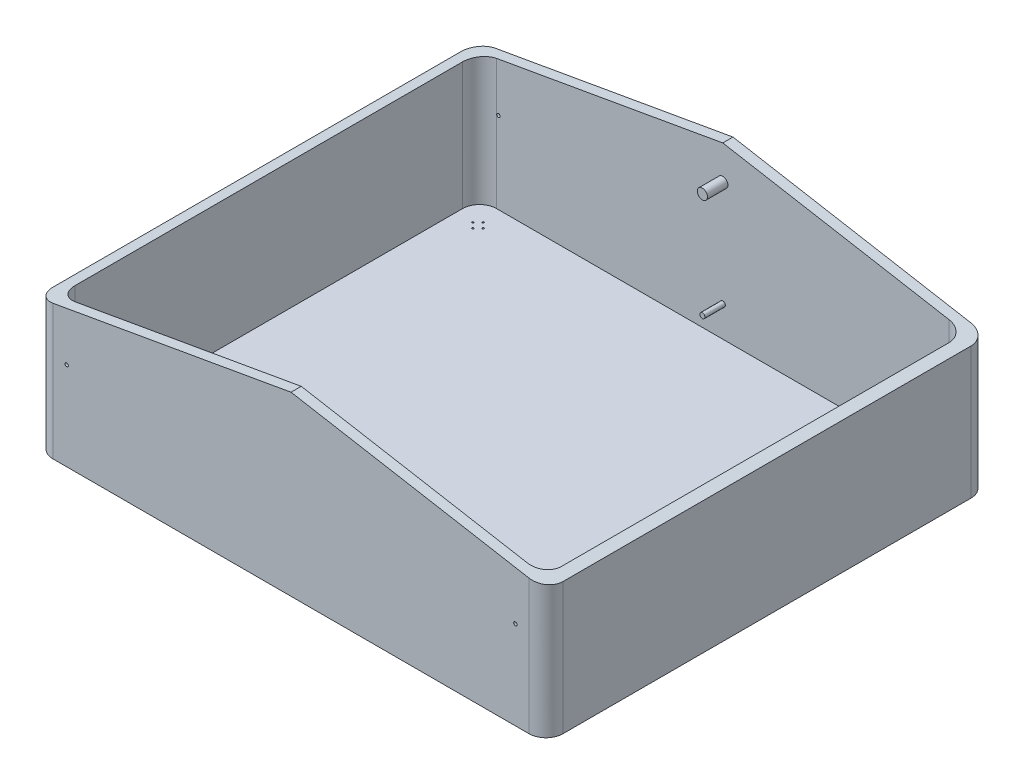
SolidWorks part; units mm, degrees
ref_plane "Спереди" through (0, 0, 0) normal (0, 0, 1) x (1, 0, 0)
ref_plane "Сверху" through (0, 0, 0) normal (0, 1, 0) x (1, 0, 0)
ref_plane "Справа" through (0, 0, 0) normal (1, 0, 0) x (0, 0, -1)
sketch "Эскиз1" plane through (0, 0, 0) normal (0, 1, 0) x (1, 0, 0)
  line L1 (-700, -650) -> (700, -650)
  line L2 (-750, -600) -> (-750, 600)
  line L3 (-700, 650) -> (700, 650)
  line L4 (750, -600) -> (750, 600)
  line L5 (-750, -650) -> (750, 650) construction
  line L6 (-750, 650) -> (750, -650) construction
  arc A0 (-700, -650) -> (-750, -600) centre (-700, -600) cw
  arc A1 (700, -650) -> (750, -600) centre (700, -600) ccw
  arc A2 (700, 650) -> (750, 600) centre (700, 600) cw
  arc A3 (-750, 600) -> (-700, 650) centre (-700, 600) cw
  point P0 (0, 0)
  dimension "D3" = 50
  dimension "D1" = 1300
  dimension "D2" = 1500
extrude "Бобышка-Вытянуть1" add sketch "Эскиз1" along normal blind 20 contours L3 A2 L4 A1 L1 A0 L2 A3
sketch "Эскиз2" plane through (0, 20, 0) normal (0, 1, 0) x (1, 0, 0)
  line L1 (700, -650) -> (-700, -650)
  line L2 (750, -600) -> (750, 600)
  line L3 (700, 650) -> (-700, 650)
  line L4 (-750, -600) -> (-750, 600)
  line L5 (750, -650) -> (-750, 650) construction
  line L6 (750, 650) -> (-750, -650) construction
  line L7 (665.3846, -620) -> (-665.3846, -620)
  line L8 (715.3846, -570) -> (715.3846, 570)
  line L9 (665.3846, 620) -> (-665.3846, 620)
  line L10 (-715.3846, -570) -> (-715.3846, 570)
  line L11 (715.3846, -620) -> (-715.3846, 620) construction
  line L12 (715.3846, 620) -> (-715.3846, -620) construction
  arc A0 (750, 600) -> (700, 650) centre (700, 600) ccw
  arc A1 (700, -650) -> (750, -600) centre (700, -600) ccw
  arc A2 (-700, 650) -> (-750, 600) centre (-700, 600) ccw
  arc A3 (-700, -650) -> (-750, -600) centre (-700, -600) cw
  arc A4 (715.3846, 570) -> (665.3846, 620) centre (665.3846, 570) ccw
  arc A5 (665.3846, -620) -> (715.3846, -570) centre (665.3846, -570) ccw
  arc A6 (-665.3846, -620) -> (-715.3846, -570) centre (-665.3846, -570) cw
  arc A7 (-665.3846, 620) -> (-715.3846, 570) centre (-665.3846, 570) ccw
  point P0 (0, 0)
  point P18 (0, 0)
  dimension "D3" = 50
  dimension "D5" = 50
  dimension "D1" = 1500
  dimension "D2" = 1300
  dimension "D4" = 30
extrude "Бобышка-Вытянуть2" add sketch "Эскиз2" along normal blind 500
sketch "Эскиз3" plane through (0, 0, 0) normal (0, -1, 0) x (1, 0, 0)
  line L0 (-750, 600) -> (-750, -600) construction
  line L1 (-650, -550) -> (650, -550)
  line L2 (-650, -550) -> (-650, 550)
  line L3 (-650, 550) -> (650, 550)
  line L4 (650, -550) -> (650, 550)
  line L5 (-650, -550) -> (650, 550) construction
  line L6 (-650, 550) -> (650, -550) construction
  line L7 (-700, 650) -> (700, 650) construction
  line L8 (0, 0) -> (650, 0) construction
  line L9 (0, 0) -> (0, 550) construction
  circle A0 centre (-650, 550) radius 15
  circle A1 centre (-650, 535) radius 2.5
  circle A2 centre (-665, 550) radius 2.5
  circle A3 centre (-650, 565) radius 2.5
  circle A4 centre (-635, 550) radius 2.5
  circle A5 centre (650, 535) radius 2.5
  circle A6 centre (635, 550) radius 2.5
  circle A7 centre (665, 550) radius 2.5
  circle A8 centre (650, 565) radius 2.5
  circle A9 centre (650, -565) radius 2.5
  circle A10 centre (635, -550) radius 2.5
  circle A11 centre (650, -535) radius 2.5
  circle A12 centre (665, -550) radius 2.5
  circle A13 centre (-635, -550) radius 2.5
  circle A14 centre (-650, -535) radius 2.5
  circle A15 centre (-665, -550) radius 2.5
  circle A16 centre (-650, -565) radius 2.5
  point P1 (0, 0)
  point P22 (-650, 550)
  dimension "D3" = 30
  dimension "D4" = 5
  dimension "D7" = 30
  dimension "D1" = 100
  dimension "D2" = 100
  dimension "D6" = 15
  dimension "D5" = 4
extrude "Вырез-Вытянуть1" cut sketch "Эскиз3" against normal blind 250 contours A16 | A3 | A2 | A4 | A1 | A7 | A8 | A6 | A5 | A11 | A10 | A12 | A9 | A14 | A15 | A13
sketch "Эскиз4" plane through (0, 0, -650) normal (0, 0, -1) x (-1, 0, 0)
  line L0 (700, 0) -> (-700, 0) construction
  line L1 (750, 520) -> (750, 0) construction
  circle A0 centre (660, 260) radius 5
  dimension "D1" = 10
  dimension "D2" = 260
  dimension "D3" = 90
extrude "Вырез-Вытянуть2" cut sketch "Эскиз4" against normal blind 1500
ref_plane "Плоскость1" through (0, 0, 0) normal (-1, 0, 0) x (0, 0, 1)
mirror "Зеркальное отражение1" about plane through (0, 0, 0) normal (-1, 0, 0) of "Вырез-Вытянуть2"
sketch "Эскиз6" plane through (0, 0, -650) normal (0, 0, -1) x (-1, 0, 0)
  line L0 (0, 520) -> (801.1222, 378.7405)
  line L1 (-700, 520) -> (700, 520) construction
  line L2 (801.1222, 378.7405) -> (801.1222, 520)
  line L3 (801.1222, 520) -> (-801.1222, 520)
  line L5 (0, 520) -> (0, 0) construction
  line L6 (700, 0) -> (-700, 0) construction
  line L7 (-801.1222, 378.7405) -> (-801.1222, 520)
  line L8 (0, 520) -> (-801.1222, 378.7405)
  line M8 (700, 0) -> (700, 520)
  line M9 (700, 520) -> (-700, 520)
  line M10 (-700, 520) -> (-700, 0)
  dimension "D1" = 10
  dimension "D2" = 141.2595
extrude "Вырез-Вытянуть3" cut sketch "Эскиз6" against normal through all contours L8 L3 L7 M10 | L8 M9 M10 | L0 M9 M8 | L2 L3 L0 M8
sketch "Эскиз7" plane through (0, 0, 620) normal (0, 0, -1) x (-1, 0, 0)
  line L0 (0, 520) -> (0, 420)
  circle A0 centre (0, 420) radius 15
  dimension "D2" = 30
  dimension "D1" = 100
extrude "Бобышка-Вытянуть3" add sketch "Эскиз7" along normal blind 60 contours A0
ref_plane "Плоскость2" through (0, 0, 0) normal (0, 0, -1) x (-1, 0, 0)
mirror "Зеркальное отражение2" about plane through (0, 0, 0) normal (0, 0, -1) of "Бобышка-Вытянуть3"
sketch "Эскиз8" plane through (0, 0, 620) normal (0, 0, -1) x (-1, 0, 0)
  line L0 (0, 520) -> (0, 110)
  line L1 (0, 520) -> (-665.3846, 402.6747) construction
  circle A0 centre (0, 110) radius 7.5
  dimension "D2" = 15
  dimension "D1" = 410
extrude "Бобышка-Вытянуть4" add sketch "Эскиз8" along normal blind 60
mirror "Зеркальное отражение3" about plane through (0, 0, 0) normal (0, 0, -1) of "Бобышка-Вытянуть4"
